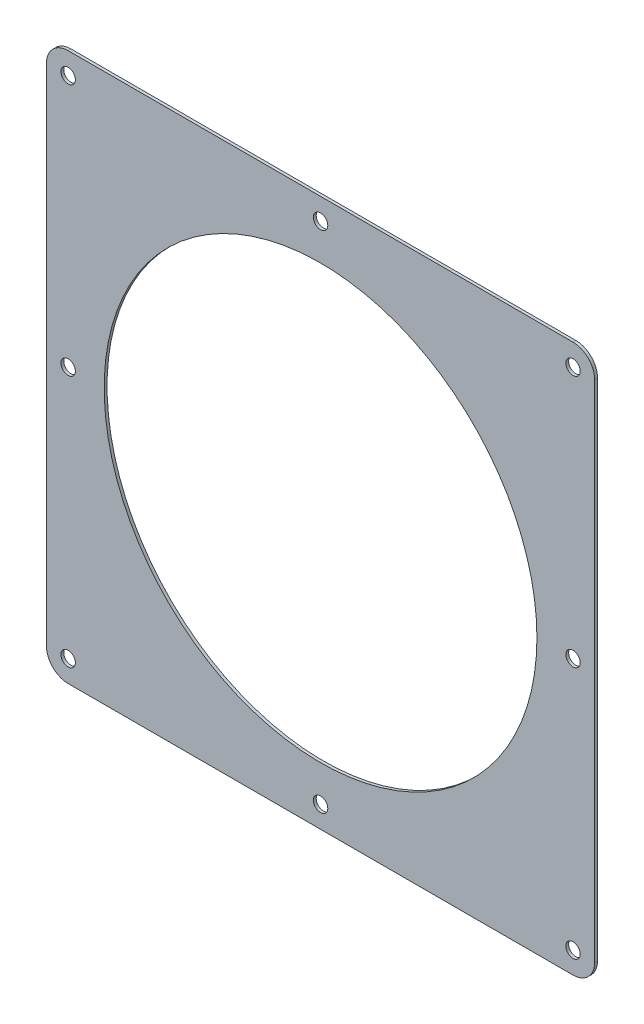
SolidWorks part; units mm, degrees
ref_plane "Front Plane" through (0, 0, 0) normal (0, 0, 1) x (1, 0, 0)
ref_plane "Top Plane" through (0, 0, 0) normal (0, 1, 0) x (1, 0, 0)
ref_plane "Right Plane" through (0, 0, 0) normal (1, 0, 0) x (0, 0, -1)
sketch "Sketch2" plane through (0, 0, 0) normal (0, 0, 1) x (1, 0, 0)
  line L0 (-175, 175) -> (175, 175) construction
  line L1 (-175, 190) -> (175, 190)
  line L2 (-190, 175) -> (-190, -175)
  line L3 (-175, -190) -> (175, -190)
  line L4 (190, 175) -> (190, -175)
  line L5 (-190, 190) -> (190, -190) construction
  line L6 (-190, -190) -> (190, 190) construction
  line L7 (175, 175) -> (175, -175) construction
  line L8 (175, -175) -> (-175, -175) construction
  line L9 (-175, -175) -> (-175, 175) construction
  line L15 (-150, 150) -> (150, -150) construction
  line L16 (-150, -150) -> (150, 150) construction
  arc A0 (-190, -175) -> (-175, -190) centre (-175, -175) ccw
  arc A1 (175, -190) -> (190, -175) centre (175, -175) ccw
  arc A2 (175, 190) -> (190, 175) centre (175, 175) cw
  arc A3 (-175, 190) -> (-190, 175) centre (-175, 175) ccw
  circle A4 centre (-175, 175) radius 5
  circle A5 centre (0, 175) radius 5
  circle A6 centre (175, 175) radius 5
  circle A14 centre (175, 0) radius 5
  circle A15 centre (-175, 0) radius 5
  circle A16 centre (-175, -175) radius 5
  circle A17 centre (0, -175) radius 5
  circle A18 centre (175, -175) radius 5
  circle A19 centre (0, 0) radius 150
  point P0 (0, 0)
  point P26 (0, 0)
  dimension "D3" = 15
  dimension "D4" = 10
  dimension "D5" = 10
  dimension "D6" = 10
  dimension "D7" = 300
  dimension "D8" = 10
  dimension "D9" = 10
  dimension "D10" = 10
  dimension "D11" = 10
  dimension "D12" = 300
  dimension "D1" = 380
  dimension "D2" = 380
extrude "Boss-Extrude1" add sketch "Sketch2" along normal blind 2
